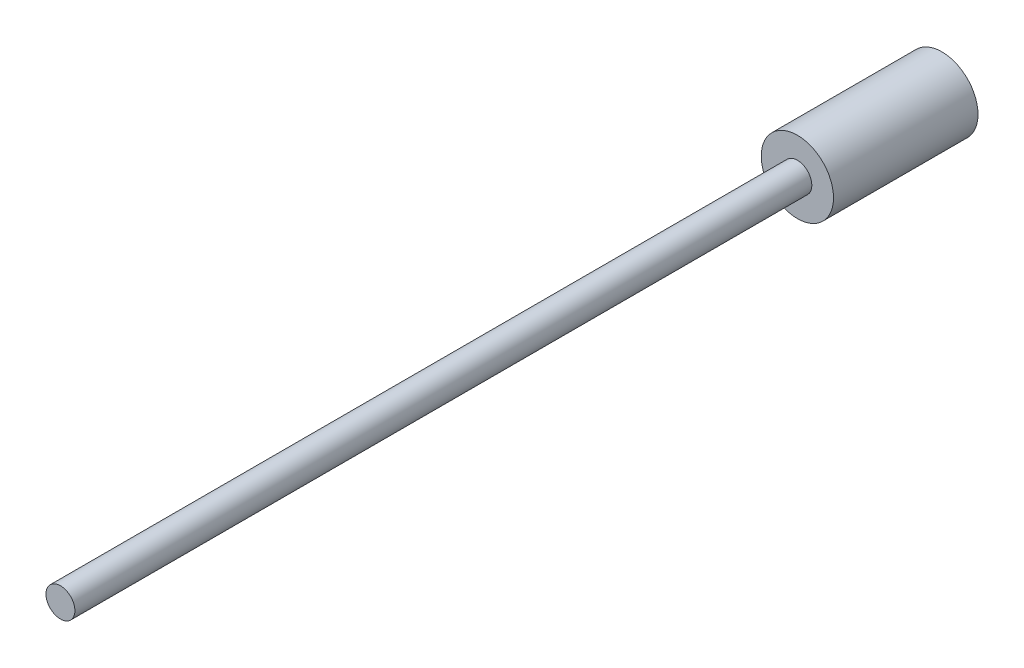
SolidWorks part; units mm, degrees
ref_plane "Front Plane" through (0, 0, 0) normal (0, 0, 1) x (1, 0, 0)
ref_plane "Top Plane" through (0, 0, 0) normal (0, 1, 0) x (1, 0, 0)
ref_plane "Right Plane" through (0, 0, 0) normal (1, 0, 0) x (0, 0, -1)
sketch "Sketch1" plane through (0, 0, 0) normal (0, 0, 1) x (1, 0, 0)
  circle A0 centre (0, 0) radius 25
  dimension "D1" = 50
extrude "Boss-Extrude1" add sketch "Sketch1" against normal blind 100
sketch "Sketch2" plane through (0, 0, 0) normal (0, 0, 1) x (1, 0, 0)
  circle A0 centre (0, 0) radius 10
  dimension "D1" = 20
extrude "Boss-Extrude2" add sketch "Sketch2" along normal blind 510
ref_plane "middle" through (0, 0, 250) normal (0, 0, 1) x (1, 0, 0)
